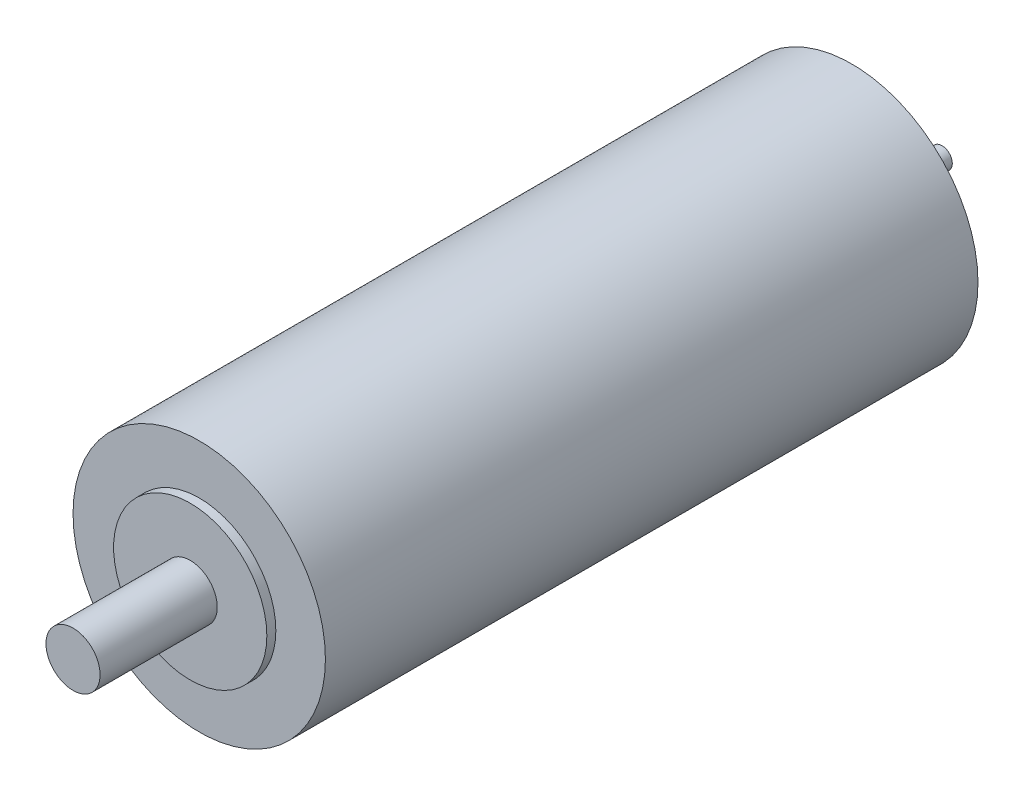
SolidWorks part; units mm, degrees
ref_plane "Front Plane" through (0, 0, 0) normal (0, 0, 1) x (1, 0, 0)
ref_plane "Top Plane" through (0, 0, 0) normal (0, 1, 0) x (1, 0, 0)
ref_plane "Right Plane" through (0, 0, 0) normal (1, 0, 0) x (0, 0, -1)
sketch "Sketch1" plane through (0, 0, 0) normal (0, 0, 1) x (1, 0, 0)
  circle A0 centre (0, 0) radius 14
  dimension "D1" = 28
extrude "Boss-Extrude1" add sketch "Sketch1" along normal mid plane 72.4
sketch "Sketch2" plane through (0, 0, 36.2) normal (0, 0, 1) x (1, 0, 0)
  circle A0 centre (0, 0) radius 8.5
  dimension "D1" = 17
extrude "Boss-Extrude2" add sketch "Sketch2" along normal mid plane 2
sketch "Sketch3" plane through (0, 0, 37.2) normal (0, 0, 1) x (1, 0, 0)
  circle A0 centre (0, 0) radius 3
  dimension "D1" = 6
extrude "Boss-Extrude3" add sketch "Sketch3" along normal blind 13
sketch "Sketch4" plane through (0, 0, 50.2) normal (0, 0, 1) x (1, 0, 0)
  line L0 (0, 3) -> (0, -2)
  line L1 (-2.2361, -2) -> (2.2361, -2)
  circle A0 centre (0, 0) radius 3 construction
  circle A1 centre (0, 0) radius 3 construction
  circle A2 centre (0, 0) radius 3
  point P13 (0, -2)
  dimension "D1" = 5
sketch "Sketch5" plane through (0, 0, -36.2) normal (0, 0, -1) x (-1, 0, 0)
  circle A0 centre (0, 0) radius 1.15
  dimension "D1" = 2.3
extrude "Boss-Extrude4" add sketch "Sketch5" along normal blind 10
